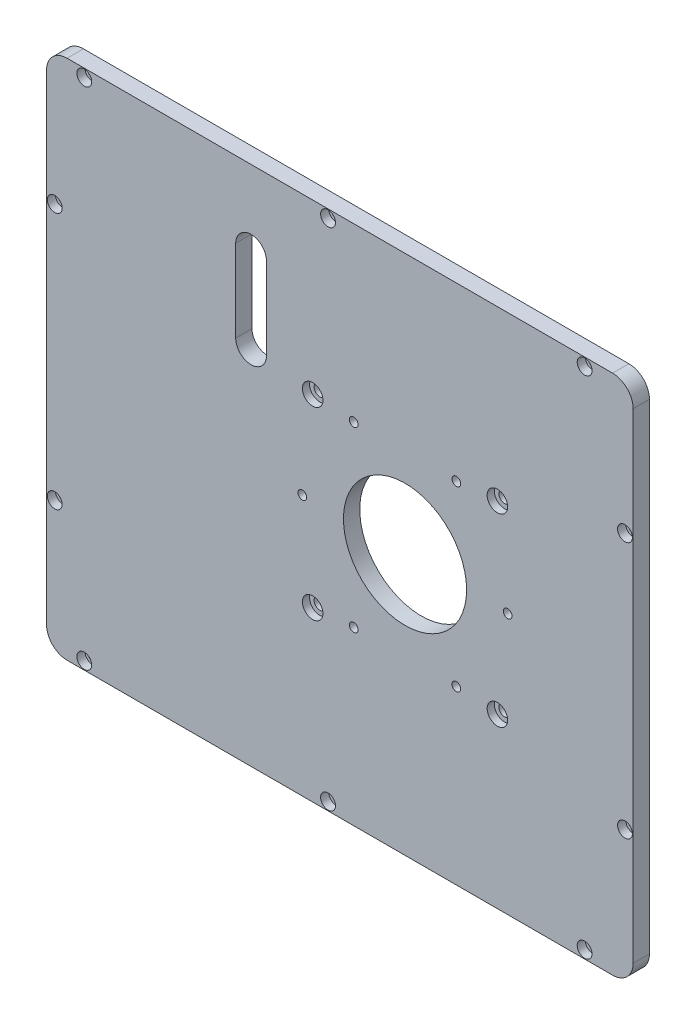
SolidWorks part; units mm, degrees
material "Aleación 6061"
ref_plane "Alzado" through (0, 0, 0) normal (0, 0, 1) x (1, 0, 0)
ref_plane "Planta" through (0, 0, 0) normal (0, 1, 0) x (1, 0, 0)
ref_plane "Vista lateral" through (0, 0, 0) normal (1, 0, 0) x (0, 0, -1)
sketch "Croquis1" plane through (0, 0, 0) normal (0, 0, 1) x (1, 0, 0)
  line L0 (-131.7, -101.6) -> (80.9, -101.6)
  line L1 (88.9, -93.6) -> (88.9, 93.6)
  line L2 (80.9, 101.6) -> (-131.7, 101.6)
  line L3 (-139.7, 93.6) -> (-139.7, -93.6)
  arc A0 (80.9, -101.6) -> (88.9, -93.6) centre (80.9, -93.6) ccw
  arc A1 (88.9, 93.6) -> (80.9, 101.6) centre (80.9, 93.6) ccw
  arc A2 (-131.7, 101.6) -> (-139.7, 93.6) centre (-131.7, 93.6) ccw
  arc A3 (-139.7, -93.6) -> (-131.7, -101.6) centre (-131.7, -93.6) ccw
  dimension "D1" = 8
  dimension "D2" = 8
  dimension "D3" = 8
  dimension "D4" = 8
  dimension "D5" = 131.7
  dimension "D6" = 101.6
  dimension "D7" = 80.9
  dimension "D8" = 101.6
  dimension "D9" = 88.9
  dimension "D10" = 93.6
  dimension "D11" = 88.9
  dimension "D12" = 93.6
  dimension "D13" = 80.9
  dimension "D14" = 101.6
  dimension "D15" = 131.7
  dimension "D16" = 101.6
  dimension "D17" = 139.7
  dimension "D18" = 93.6
  dimension "D19" = 139.7
  dimension "D20" = 93.6
extrude "Tapa_1-4in" add sketch "Croquis1" along normal blind 6.35 from offset 63.5
sketch "Croquis2" plane through (0, 0, 0) normal (0, 0, 1) x (1, 0, 0)
  circle A0 centre (0, 0) radius 24
  circle A1 centre (-36, -36) radius 2.25
  circle A2 centre (-36, 36) radius 2.25
  circle A3 centre (36, -36) radius 2.25
  circle A4 centre (36, 36) radius 2.25
  circle A5 centre (40, 0) radius 1.25
  circle A6 centre (20, 34.641) radius 1.25
  circle A7 centre (-20, 34.641) radius 1.25
  circle A8 centre (-40, 0) radius 1.25
  circle A9 centre (-20, -34.641) radius 1.25
  circle A10 centre (20, -34.641) radius 1.25
  circle A11 centre (-125, 98.425) radius 1.7
  circle A12 centre (-125, -98.425) radius 1.7
  circle A13 centre (-30, 98.425) radius 1.7
  circle A14 centre (-30, -98.425) radius 1.7
  circle A15 centre (70, 98.425) radius 1.7
  circle A16 centre (70, -98.425) radius 1.7
  circle A17 centre (-136.525, -50) radius 1.7
  circle A18 centre (-136.525, 50) radius 1.7
  circle A19 centre (85.725, -50) radius 1.7
  circle A20 centre (85.725, 50) radius 1.7
  dimension "D1" = 48
  dimension "D2" = 4.5
  dimension "D3" = 4.5
  dimension "D4" = 4.5
  dimension "D5" = 4.5
  dimension "D6" = 2.5
  dimension "D7" = 2.5
  dimension "D8" = 2.5
  dimension "D9" = 2.5
  dimension "D10" = 2.5
  dimension "D11" = 2.5
  dimension "D12" = 3.4
  dimension "D13" = 3.4
  dimension "D14" = 3.4
  dimension "D15" = 3.4
  dimension "D16" = 3.4
  dimension "D17" = 3.4
  dimension "D18" = 3.4
  dimension "D19" = 3.4
  dimension "D20" = 3.4
  dimension "D21" = 3.4
  dimension "D22" = 36
  dimension "D23" = 36
  dimension "D24" = 36
  dimension "D25" = 36
  dimension "D26" = 36
  dimension "D27" = 36
  dimension "D28" = 36
  dimension "D29" = 36
  dimension "D30" = 40
  dimension "D31" = 20
  dimension "D32" = 34.641
  dimension "D33" = 20
  dimension "D34" = 34.641
  dimension "D35" = 40
  dimension "D36" = 20
  dimension "D37" = 34.641
  dimension "D38" = 20
  dimension "D39" = 34.641
  dimension "D40" = 125
  dimension "D41" = 98.425
  dimension "D42" = 125
  dimension "D43" = 98.425
  dimension "D44" = 30
  dimension "D45" = 98.425
  dimension "D46" = 30
  dimension "D47" = 98.425
  dimension "D48" = 70
  dimension "D49" = 98.425
  dimension "D50" = 70
  dimension "D51" = 98.425
  dimension "D52" = 136.525
  dimension "D53" = 50
  dimension "D54" = 136.525
  dimension "D55" = 50
  dimension "D56" = 85.725
  dimension "D57" = 50
  dimension "D58" = 85.725
  dimension "D59" = 50
extrude "Paso_M1_rosca_aro_separadores_y_tornillos" cut sketch "Croquis2" along normal blind 6.35 from offset 63.5
sketch "Croquis3" plane through (0, 0, 0) normal (0, 0, 1) x (1, 0, 0)
  circle A0 centre (-36, -36) radius 4
  circle A1 centre (-36, 36) radius 4
  circle A2 centre (36, -36) radius 4
  circle A3 centre (36, 36) radius 4
  dimension "D1" = 8
  dimension "D2" = 8
  dimension "D3" = 8
  dimension "D4" = 8
  dimension "D5" = 36
  dimension "D6" = 36
  dimension "D7" = 36
  dimension "D8" = 36
  dimension "D9" = 36
  dimension "D10" = 36
  dimension "D11" = 36
  dimension "D12" = 36
extrude "Refrentado_M4_cabeza_baja" cut sketch "Croquis3" along normal blind 2.8 from offset 67.05
sketch "Croquis4" plane through (0, 0, 0) normal (0, 0, 1) x (1, 0, 0)
  circle A0 centre (-125, 98.425) radius 2.9
  circle A1 centre (-125, -98.425) radius 2.9
  circle A2 centre (-30, 98.425) radius 2.9
  circle A3 centre (-30, -98.425) radius 2.9
  circle A4 centre (70, 98.425) radius 2.9
  circle A5 centre (70, -98.425) radius 2.9
  circle A6 centre (-136.525, -50) radius 2.9
  circle A7 centre (-136.525, 50) radius 2.9
  circle A8 centre (85.725, -50) radius 2.9
  circle A9 centre (85.725, 50) radius 2.9
  dimension "D1" = 5.8
  dimension "D2" = 5.8
  dimension "D3" = 5.8
  dimension "D4" = 5.8
  dimension "D5" = 5.8
  dimension "D6" = 5.8
  dimension "D7" = 5.8
  dimension "D8" = 5.8
  dimension "D9" = 5.8
  dimension "D10" = 5.8
  dimension "D11" = 125
  dimension "D12" = 98.425
  dimension "D13" = 125
  dimension "D14" = 98.425
  dimension "D15" = 30
  dimension "D16" = 98.425
  dimension "D17" = 30
  dimension "D18" = 98.425
  dimension "D19" = 70
  dimension "D20" = 98.425
  dimension "D21" = 70
  dimension "D22" = 98.425
  dimension "D23" = 136.525
  dimension "D24" = 50
  dimension "D25" = 136.525
  dimension "D26" = 50
  dimension "D27" = 85.725
  dimension "D28" = 50
  dimension "D29" = 85.725
  dimension "D30" = 50
extrude "Refrentado_M3" cut sketch "Croquis4" along normal blind 3.2 from offset 66.65
sketch "Croquis5" plane through (0, 0, 0) normal (0, 0, 1) x (1, 0, 0)
  line L0 (-66, 40) -> (-66, 72)
  line L1 (-54, 72) -> (-54, 40)
  arc A0 (-66, 72) -> (-54, 72) centre (-60, 72) cw
  arc A1 (-54, 40) -> (-66, 40) centre (-60, 40) cw
  dimension "D1" = 6
  dimension "D2" = 6
  dimension "D3" = 66
  dimension "D4" = 40
  dimension "D5" = 66
  dimension "D6" = 72
  dimension "D7" = 54
  dimension "D8" = 72
  dimension "D9" = 54
  dimension "D10" = 40
extrude "Ranura_cables_potencia_CAN" cut sketch "Croquis5" along normal blind 6.35 from offset 63.5
sketch "Croquis6" plane through (0, 0, 0) normal (0, 0, 1) x (1, 0, 0)
  circle A0 centre (40, 0) radius 1.7
  circle A1 centre (20, 34.641) radius 1.7
  circle A2 centre (-20, 34.641) radius 1.7
  circle A3 centre (-40, 0) radius 1.7
  circle A4 centre (-20, -34.641) radius 1.7
  circle A5 centre (20, -34.641) radius 1.7
  dimension "D1" = 3.4
  dimension "D2" = 3.4
  dimension "D3" = 3.4
  dimension "D4" = 3.4
  dimension "D5" = 3.4
  dimension "D6" = 3.4
  dimension "D7" = 40
  dimension "D8" = 20
  dimension "D9" = 34.641
  dimension "D10" = 20
  dimension "D11" = 34.641
  dimension "D12" = 40
  dimension "D13" = 20
  dimension "D14" = 34.641
  dimension "D15" = 20
  dimension "D16" = 34.641
extrude "Paso_M3_aro_tuerca" cut sketch "Croquis6" along normal blind 6.35 from offset 63.5
sketch "Croquis7" plane through (0, 0, 0) normal (0, 0, 1) x (1, 0, 0)
  line L0 (-62, -14) -> (-62, 14)
  line L1 (-48, 14) -> (-48, -14)
  arc A0 (-62, 14) -> (-48, 14) centre (-55, 14) cw
  arc A1 (-48, -14) -> (-62, -14) centre (-55, -14) cw
  dimension "D1" = 7
  dimension "D2" = 7
  dimension "D3" = 62
  dimension "D4" = 14
  dimension "D5" = 62
  dimension "D6" = 14
  dimension "D7" = 48
  dimension "D8" = 14
  dimension "D9" = 48
  dimension "D10" = 14
